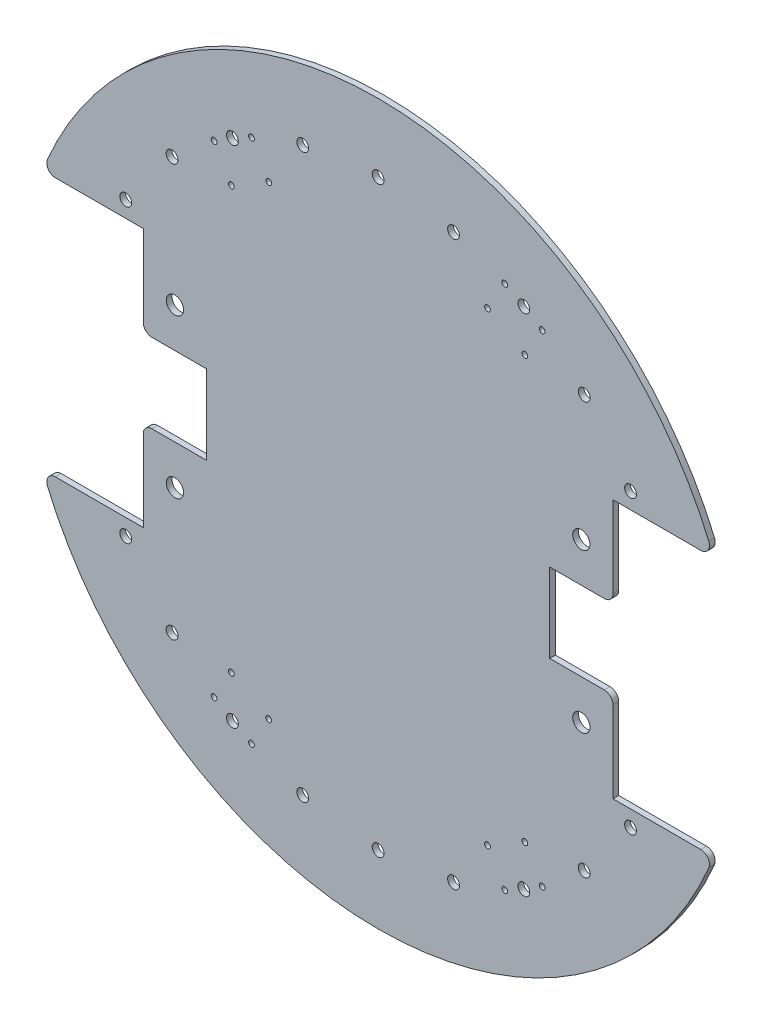
SolidWorks part; units mm, degrees
material "1345 Alloy"
ref_plane "Front Plane" through (0, 0, 0) normal (0, 0, 1) x (1, 0, 0)
ref_plane "Top Plane" through (0, 0, 0) normal (0, 1, 0) x (1, 0, 0)
ref_plane "Right Plane" through (0, 0, 0) normal (1, 0, 0) x (0, 0, -1)
sketch "Sketch1" plane through (0, 0, 0) normal (0, 0, 1) x (1, 0, 0)
  line L0 (-163.2381, -33.5) -> (-163.2381, -90)
  line L2 (163.2381, -90) -> (163.2381, -33.5)
  line L3 (163.2381, 33.5) -> (163.2381, 90)
  line L7 (-224.3212, 90) -> (-163.2381, 90)
  line L8 (-224.3212, -90) -> (-163.2381, -90)
  line L9 (-163.2381, 90) -> (-163.2381, 33.5)
  line L10 (-119.2381, 27.5) -> (-119.2381, -27.5)
  line L12 (163.2381, -90) -> (224.3212, -90)
  line L13 (163.2381, 90) -> (224.3212, 90)
  line L15 (157.2381, -27.5) -> (119.2381, -27.5)
  line L20 (-157.2381, -27.5) -> (-119.2381, -27.5)
  line L28 (-157.2381, 27.5) -> (-119.2381, 27.5)
  line L29 (119.2381, 27.5) -> (119.2381, -27.5)
  line L30 (157.2381, 27.5) -> (119.2381, 27.5)
  arc A0 (229.8373, 98.3607) -> (-229.8373, 98.3607) centre (0, 0) ccw
  arc A3 (-229.8373, -98.3607) -> (229.8373, -98.3607) centre (0, 0) ccw
  arc A4 (-229.8373, -98.3607) -> (-224.3212, -90) centre (-224.3212, -96) cw
  arc A5 (229.8373, -98.3607) -> (224.3212, -90) centre (224.3212, -96) ccw
  arc A6 (229.8373, 98.3607) -> (224.3212, 90) centre (224.3212, 96) cw
  arc A7 (-229.8373, 98.3607) -> (-224.3212, 90) centre (-224.3212, 96) ccw
  arc A18 (-163.2381, -33.5) -> (-157.2381, -27.5) centre (-157.2381, -33.5) cw
  arc A19 (163.2381, 33.5) -> (157.2381, 27.5) centre (157.2381, 33.5) cw
  arc A20 (163.2381, -33.5) -> (157.2381, -27.5) centre (157.2381, -33.5) ccw
  arc A21 (-157.2381, 27.5) -> (-163.2381, 33.5) centre (-157.2381, 33.5) cw
  circle A22 centre (-141.2381, 55) radius 6
  circle A23 centre (-141.2381, -55) radius 6
  circle A24 centre (141.2381, -55) radius 6
  circle A25 centre (141.2381, 55) radius 6
  circle A26 centre (0, -202.5562) radius 4.1
  circle A27 centre (-52.4254, -195.6542) radius 4.1
  circle A28 centre (-101.2781, -175.4188) radius 4.1
  circle A29 centre (-143.2288, -143.2288) radius 4.1
  circle A30 centre (-175.4188, -101.2781) radius 4.1
  circle A34 centre (-175.4188, 101.2781) radius 4.1
  circle A35 centre (-143.2288, 143.2288) radius 4.1
  circle A36 centre (-101.2781, 175.4188) radius 4.1
  circle A37 centre (-52.4254, 195.6542) radius 4.1
  circle A38 centre (0, 202.5562) radius 4.1
  circle A39 centre (52.4254, 195.6542) radius 4.1
  circle A40 centre (101.2781, 175.4188) radius 4.1
  circle A41 centre (143.2288, 143.2288) radius 4.1
  circle A42 centre (175.4188, 101.2781) radius 4.1
  circle A46 centre (175.4188, -101.2781) radius 4.1
  circle A47 centre (143.2288, -143.2288) radius 4.1
  circle A48 centre (101.2781, -175.4188) radius 4.1
  circle A49 centre (52.4254, -195.6542) radius 4.1
  point P8 (0, 0)
  point P13 (0, 0)
  point P45 (0, 0)
  point P58 (0, 0)
  point P68 (0, 0)
  point P115 (0, 0)
  dimension "D1" = 500
  dimension "D4" = 6
  dimension "D5" = 6
  dimension "D11" = 12
  dimension "D12" = 12
  dimension "D13" = 8.2
  dimension "D2" = 55
  dimension "D7" = 55
extrude "Boss-Extrude1" add sketch "Sketch1" along normal blind 4
sketch "Sketch2" plane through (0, 0, 4) normal (0, 0, 1) x (1, 0, 0)
  line L0 (0, 0) -> (163.2381, 0) construction
  line L1 (-233.2381, 90) -> (-163.2381, -90) construction
  line L11 (163.2381, -90) -> (163.2381, 90)
  line L12 (-163.2381, 0) -> (0, 0) construction
  line L13 (163.2381, 90) -> (233.2381, -90) construction
  line L14 (163.2381, 90) -> (233.2381, 90)
  line L15 (163.2381, -90) -> (233.2381, -90)
  line L16 (-233.2381, 90) -> (-163.2381, 90)
  line L18 (-233.2381, -90) -> (-163.2381, -90)
  line L19 (-163.2381, 90) -> (-163.2381, -90)
  line L20 (-163.2381, 90) -> (-233.2381, -90) construction
  line L21 (233.2381, 90) -> (163.2381, -90) construction
  circle A0 centre (0, 0) radius 250 construction
  arc A2 (-233.2381, 90) -> (-233.2381, -90) centre (0, 0) ccw
  arc A3 (233.2381, -90) -> (233.2381, 90) centre (0, 0) ccw
  point P18 (0, 0)
  dimension "D1" = 70
  dimension "D3" = 70
extrude "Cut-Extrude1" [suppressed] cut sketch "Sketch2" against normal blind 10
sketch "Sketch5" plane through (0, 0, 4) normal (0, 0, 1) x (1, 0, 0)
  line L8 (-113.9904, 167.4371) -> (-101.9904, 146.6525) construction
  line L10 (88.0096, 182.4371) -> (76.0096, 161.6525) construction
  line L11 (-101.9904, 146.6525) -> (-76.0096, 161.6525) construction
  line L14 (-76.0096, 161.6525) -> (-88.0096, 182.4371) construction
  line L18 (-88.0096, 182.4371) -> (-113.9904, 167.4371) construction
  line L19 (-88.0096, 182.4371) -> (-101.9904, 146.6525) construction
  line L20 (-113.9904, 167.4371) -> (-76.0096, 161.6525) construction
  line L21 (0, 0) -> (-95, 164.5448) construction
  line L22 (76.0096, 161.6525) -> (101.9904, 146.6525) construction
  line L23 (101.9904, 146.6525) -> (113.9904, 167.4371) construction
  line L24 (113.9904, 167.4371) -> (88.0096, 182.4371) construction
  line L29 (113.9904, 167.4371) -> (76.0096, 161.6525) construction
  line L34 (88.0096, 182.4371) -> (101.9904, 146.6525) construction
  line L39 (0, 0) -> (95, 164.5448) construction
  line L59 (113.9904, -167.4371) -> (101.9904, -146.6525) construction
  line L64 (101.9904, -146.6525) -> (76.0096, -161.6525) construction
  line L69 (76.0096, -161.6525) -> (88.0096, -182.4371) construction
  line L74 (88.0096, -182.4371) -> (113.9904, -167.4371) construction
  line L84 (88.0096, -182.4371) -> (101.9904, -146.6525) construction
  line L85 (113.9904, -167.4371) -> (76.0096, -161.6525) construction
  line L86 (0, 0) -> (95, -164.5448) construction
  line L87 (-88.0096, -182.4371) -> (-76.0096, -161.6525) construction
  line L88 (-76.0096, -161.6525) -> (-101.9904, -146.6525) construction
  line L89 (-101.9904, -146.6525) -> (-113.9904, -167.4371) construction
  line L90 (-113.9904, -167.4371) -> (-88.0096, -182.4371) construction
  line L91 (-113.9904, -167.4371) -> (-76.0096, -161.6525) construction
  line L92 (-88.0096, -182.4371) -> (-101.9904, -146.6525) construction
  line L93 (0, 0) -> (-95, -164.5448) construction
  line L101 (-202, -15) -> (-178, -15) construction
  line L102 (-178, -15) -> (-178, 15) construction
  line L103 (-178, 15) -> (-202, 15) construction
  line L104 (-202, 15) -> (-202, -15) construction
  line L105 (-202, 15) -> (-178, -15) construction
  line L106 (-202, -15) -> (-178, 15) construction
  line L107 (0, 0) -> (-190, 0) construction
  line L108 (202, 15) -> (178, 15) construction
  line L109 (178, 15) -> (178, -15) construction
  line L110 (178, -15) -> (202, -15) construction
  line L111 (202, -15) -> (202, 15) construction
  line L112 (202, -15) -> (178, 15) construction
  line L113 (202, 15) -> (178, -15) construction
  line L114 (0, 0) -> (190, 0) construction
  circle A62 centre (-101.9904, 146.6525) radius 2
  circle A63 centre (-76.0096, 161.6525) radius 2
  circle A64 centre (-113.9904, 167.4371) radius 2
  circle A65 centre (-88.0096, 182.4371) radius 2
  circle A70 centre (76.0096, 161.6525) radius 2
  circle A71 centre (101.9904, 146.6525) radius 2
  circle A72 centre (88.0096, 182.4371) radius 2
  circle A73 centre (113.9904, 167.4371) radius 2
  circle A82 centre (101.9904, -146.6525) radius 2
  circle A83 centre (76.0096, -161.6525) radius 2
  circle A84 centre (113.9904, -167.4371) radius 2
  circle A85 centre (88.0096, -182.4371) radius 2
  circle A86 centre (-76.0096, -161.6525) radius 2
  circle A87 centre (-101.9904, -146.6525) radius 2
  circle A88 centre (-88.0096, -182.4371) radius 2
  circle A89 centre (-113.9904, -167.4371) radius 2
  circle A94 centre (-178, -15) radius 2 [skipped]
  circle A95 centre (-178, 15) radius 2 [skipped]
  circle A96 centre (-202, -15) radius 2 [skipped]
  circle A97 centre (-202, 15) radius 2 [skipped]
  circle A98 centre (178, 15) radius 2 [skipped]
  circle A99 centre (178, -15) radius 2 [skipped]
  circle A100 centre (202, 15) radius 2 [skipped]
  circle A101 centre (202, -15) radius 2 [skipped]
  point P5 (0, 0)
  point P6 (0, 0)
  point P15 (0, 0)
  point P17 (0, 0)
  point P18 (0, 0)
  point P27 (0, 0)
  point P29 (0, 0)
  point P30 (0, 0)
  point P33 (-141.1925, 81.5175)
  point P35 (0, 0)
  point P41 (0, 0)
  point P43 (0, 0)
  point P44 (0, 0)
  point P49 (0, 0)
  point P54 (0, 0)
  point P56 (0, 0)
  point P57 (0, 0)
  point P66 (0, 0)
  point P67 (0, 0)
  point P193 (0, 0)
  dimension "D1" = 6
extrude "Cut-Extrude3" cut sketch "Sketch5" against normal blind 10
sketch "Sketch12" plane through (0, 0, 4) normal (0, 0, 1) x (1, 0, 0)
  line L0 (-163.2381, 0) -> (0, 0) construction
  line L1 (207.2381, -25) -> (119.2381, -25)
  line L2 (207.2381, -25) -> (207.2381, 25)
  line L3 (207.2381, 25) -> (119.2381, 25)
  line L4 (-207.2381, 25) -> (-119.2381, 25)
  line L6 (-207.2381, 25) -> (-207.2381, -25)
  line L7 (-207.2381, -25) -> (-119.2381, -25)
  line L8 (-119.2381, 25) -> (-119.2381, -25)
  line L9 (-207.2381, 25) -> (-119.2381, -25) construction
  line L10 (-207.2381, -25) -> (-119.2381, 25) construction
  line L11 (119.2381, -25) -> (119.2381, 25)
  line L12 (163.2381, 0) -> (0, 0) construction
  line L13 (207.2381, -25) -> (119.2381, 25) construction
  line L14 (207.2381, 25) -> (119.2381, -25) construction
  line L15 (0, 0) -> (0, -202.5562) construction
  circle A0 centre (-141.2381, 55) radius 6
  circle A1 centre (-141.2381, -55) radius 6
  circle A2 centre (141.2381, -55) radius 6
  circle A3 centre (141.2381, 55) radius 6
  circle A5 centre (0, -202.5562) radius 4.1
  circle A6 centre (-52.4254, -195.6542) radius 4.1
  circle A7 centre (-101.2781, -175.4188) radius 4.1
  circle A8 centre (-143.2288, -143.2288) radius 4.1
  circle A9 centre (-175.4188, -101.2781) radius 4.1
  circle A10 centre (-195.6542, -52.4254) radius 4.1
  circle A11 centre (-202.5562, 0) radius 4.1
  circle A12 centre (-195.6542, 52.4254) radius 4.1
  circle A13 centre (-175.4188, 101.2781) radius 4.1
  circle A14 centre (-143.2288, 143.2288) radius 4.1
  circle A15 centre (-101.2781, 175.4188) radius 4.1
  circle A16 centre (-52.4254, 195.6542) radius 4.1
  circle A17 centre (0, 202.5562) radius 4.1
  circle A18 centre (52.4254, 195.6542) radius 4.1
  circle A19 centre (101.2781, 175.4188) radius 4.1
  circle A20 centre (143.2288, 143.2288) radius 4.1
  circle A21 centre (175.4188, 101.2781) radius 4.1
  circle A22 centre (195.6542, 52.4254) radius 4.1
  circle A23 centre (202.5562, 0) radius 4.1
  circle A24 centre (195.6542, -52.4254) radius 4.1
  circle A25 centre (175.4188, -101.2781) radius 4.1
  circle A26 centre (143.2288, -143.2288) radius 4.1
  circle A27 centre (101.2781, -175.4188) radius 4.1
  circle A28 centre (52.4254, -195.6542) radius 4.1
  point P23 (0, 0)
  point P76 (0, 0)
  dimension "D8" = 12
  dimension "D9" = 12
  dimension "D3" = 8.2
  dimension "D1" = 88
  dimension "D2" = 2
  dimension "D4" = 50
  dimension "D5" = 24
extrude "Cut-Extrude7" [suppressed] cut sketch "Sketch12" against normal through all
